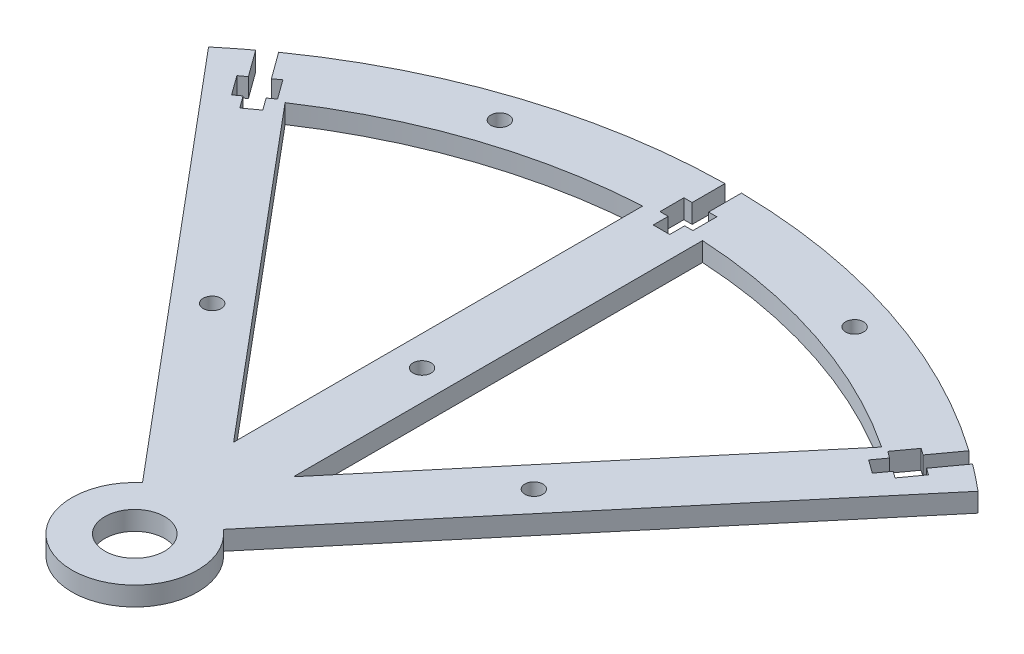
SolidWorks part; units mm, degrees
ref_plane "Front Plane" through (0, 0, 0) normal (0, 0, 1) x (1, 0, 0)
ref_plane "Top Plane" through (0, 0, 0) normal (0, 1, 0) x (1, 0, 0)
ref_plane "Right Plane" through (0, 0, 0) normal (1, 0, 0) x (0, 0, -1)
sketch "Sketch1" plane through (0, 0, 0) normal (0, 1, 0) x (1, 0, 0)
  line L0 (-64.2788, 0) -> (-6.7493, -68.561)
  line L2 (-64.2788, 0) -> (64.2788, 0) construction
  line L3 (-49.8322, -1.6595) -> (-5, -55.0884)
  line L4 (5, -55.0884) -> (49.8322, -1.6595)
  line L7 (-5, 13.2566) -> (-5, -55.0884)
  line L8 (5, -55.0884) -> (5, 13.2566)
  line L39 (6.7493, -68.561) -> (64.2788, 0)
  arc A0 (-64.2788, 0) -> (64.2788, 0) centre (0, -76.6044) cw
  arc A1 (-49.8322, -1.6595) -> (-5, 13.2566) centre (0, -76.6044) cw
  arc A3 (5, 13.2566) -> (49.8322, -1.6595) centre (0, -76.6044) cw
  circle A17 centre (0, -76.6044) radius 5
  arc A18 (-6.7493, -68.561) -> (6.7493, -68.561) centre (0, -76.6044) ccw
  point P0 (0, 0)
  point P2 (0, 0)
  dimension "D17" = 10
  dimension "D18" = 21
  dimension "D8" = 10
  dimension "D2" = 100
  dimension "D3" = 80
  dimension "D4" = 10
  dimension "D5" = 5
extrude "Boss-Extrude1" add sketch "Sketch1" along normal blind 3.175
sketch "Sketch6" plane through (0, 3.175, 0) normal (0, 1, 0) x (1, 0, 0)
  line L0 (-1.375, 11.3956) -> (-1.375, 23.3956)
  line L1 (-1.375, 11.3956) -> (1.375, 11.3956)
  line L2 (-1.375, 23.3956) -> (1.375, 23.3956)
  line L3 (1.375, 11.3956) -> (1.375, 23.3956)
  line L4 (-1.375, 11.3956) -> (1.375, 23.3956) construction
  line L5 (-1.375, 23.3956) -> (1.375, 11.3956) construction
  line L10 (0, 23.3956) -> (0, -76.6044) construction
  line L11 (-2.75, 13.8956) -> (-2.75, 17.8956)
  line L12 (-2.75, 13.8956) -> (2.75, 13.8956)
  line L13 (-2.75, 17.8956) -> (2.75, 17.8956)
  line L14 (2.75, 13.8956) -> (2.75, 17.8956)
  line L15 (-2.75, 13.8956) -> (2.75, 17.8956) construction
  line L16 (-2.75, 17.8956) -> (2.75, 13.8956) construction
  arc A0 (64.2788, 0) -> (-64.2788, 0) centre (0, -76.6044) ccw construction
  point P1 (0, 17.3956)
  point P3 (0, 15.8956)
  arc M26 (64.2788, 0) -> (-64.2788, 0) centre (0, -76.6044) ccw
  dimension "D1" = 2.75
  dimension "D2" = 4
  dimension "D3" = 5.5
  dimension "D4" = 12
  dimension "D5" = 2.5
extrude "Cut-Extrude4" cut sketch "Sketch6" against normal through all contours L12 L0 L1 L3 | L13 L0 L12 L3 | L13 L11 L12 L0 | L0 L13 L3 M26 | L12 L14 L13 L3
pattern_circular "CirPattern1" count 2 every 36 about axis through (0, 0, 76.6044) along (0, 1, 0) of "Cut-Extrude4"
hole_wizard "Ø3.0 (3) Diameter Hole1" positions "Sketch7" profile "Sketch8" hole size "Ø3.0" standard "ANSI Metric" end condition up to next
sketch "Sketch7" plane through (0, 3.175, 0) normal (0, 1, 0) x (1, 0, 0)
  line L0 (-1.375, 11.3956) -> (1.375, 11.3956) construction
  line L1 (50.6127, -4.6027) -> (52.8375, -6.2192) construction
  line L2 (-52.8375, -6.2192) -> (-50.6127, -4.6027) construction
  line L3 (-30.7044, -40.0124) -> (-23.044, -33.5845) construction
  line L4 (-64.2788, 0) -> (-6.7493, -68.561) construction
  line L5 (-49.8322, -1.6595) -> (-5, -55.0884) construction
  line L7 (30.7044, -40.0124) -> (23.044, -33.5845) construction
  line L8 (6.7493, -68.561) -> (64.2788, 0) construction
  line L9 (5, -55.0884) -> (49.8322, -1.6595) construction
  line L11 (-1.375, 17.8956) -> (-1.375, 23.3861) construction
  line L12 (-54.4333, 0.6559) -> (-57.6606, 5.0978) construction
  line L13 (1.375, 17.8956) -> (1.375, 23.3861) construction
  line L14 (54.4333, 0.6559) -> (57.6606, 5.0978) construction
  circle A0 centre (0, -76.6044) radius 95 construction
  arc A2 (-1.375, 18.3856) -> (-54.7214, 1.0523) centre (0, -76.6044) ccw construction
  arc A3 (1.375, 18.3856) -> (54.7214, 1.0523) centre (0, -76.6044) cw construction
  point P0 (0, -28.6044)
  point P2 (-26.8742, -36.7984)
  point P4 (26.8742, -36.7984)
  point P6 (30.1914, 13.4704)
  point P8 (-29.3566, 13.7459)
  dimension "D4" = 190
  dimension "D1" = 40
  dimension "D2" = 40
  dimension "D3" = 40
sketch "Sketch8" plane through (0, 3.175, 28.6044) normal (1, 0, 0) x (0, 0, 1)
  line L0 (0, 0) -> (0, 3.175)
  line L1 (0, 3.175) -> (1.5, 3.175)
  line L2 (1.5, 3.175) -> (1.5, 0)
  line L5 (1.5, 0) -> (0, 0)
  line L11 (0, -6.35) -> (0, 107.95) construction
  dimension "Thru Hole Dia." = 3
  dimension "Thru Hole Depth" = 3.175
